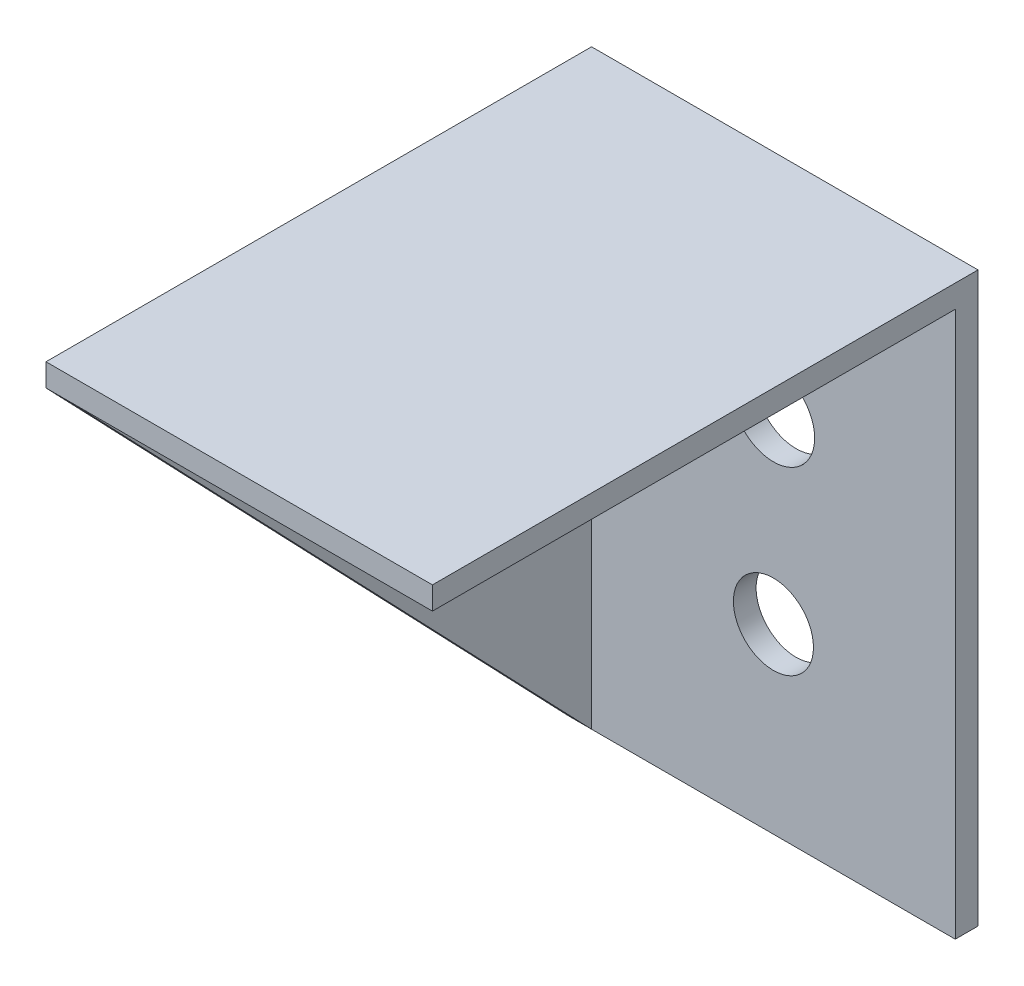
SolidWorks part; units mm, degrees
ref_plane "前视基准面" through (0, 0, 0) normal (0, 0, 1) x (1, 0, 0)
ref_plane "上视基准面" through (0, 0, 0) normal (0, 1, 0) x (1, 0, 0)
ref_plane "右视基准面" through (0, 0, 0) normal (1, 0, 0) x (0, 0, -1)
sketch "草图1" plane through (0, 0, 0) normal (0, 0, 1) x (1, 0, 0)
  line L1 (-1.8531, 2.9266) -> (0.1469, 2.9266)
  line L2 (-1.8531, 2.9266) -> (-1.8531, -0.0734)
  line L3 (-1.8531, -0.0734) -> (0.1469, -0.0734)
  line L4 (0.1469, 2.9266) -> (0.1469, -0.0734)
  line L5 (-1.8531, 2.9266) -> (0.1469, -0.0734) construction
  line L6 (-1.8531, -0.0734) -> (0.1469, 2.9266) construction
  point P0 (-0.8531, 1.4266)
  dimension "D1" = 3
  dimension "D2" = 2
extrude "凸台-拉伸1" add sketch "草图1" along normal blind 0.125
sketch "草图2" plane through (0, 2.9266, 0) normal (0, 1, 0) x (1, 0, 0)
  line L1 (-1.8531, 0) -> (0.1469, 0)
  line L2 (-1.8531, 0) -> (-1.8531, -3)
  line L3 (-1.8531, -3) -> (0.1469, -3)
  line L4 (0.1469, 0) -> (0.1469, -3)
  dimension "D1" = 2
  dimension "D2" = 3
extrude "凸台-拉伸2" add sketch "草图2" along normal blind 0.125
sketch "草图3" plane through (-1.8531, 0, 0) normal (-1, 0, 0) x (0, 0, 1)
  line L0 (0, 3.0516) -> (0, -0.0734)
  line L1 (0, -0.0734) -> (0.125, -0.0734)
  line L2 (0.125, -0.0734) -> (3, 2.9266)
  line L3 (3, 2.9266) -> (3, 3.0516)
  line L4 (3, 3.0516) -> (0, 3.0516)
extrude "凸台-拉伸3" add sketch "草图3" along normal blind 0.125
sketch "草图4" plane through (0, 0, 0.125) normal (0, 0, 1) x (1, 0, 0)
  line L0 (-1.8531, 2.9266) -> (-1.8531, -0.0734) construction
  line L1 (-1.8531, -0.0734) -> (0.1469, -0.0734) construction
  circle A0 centre (-0.8531, 0.9266) radius 0.2201
  circle A1 centre (-0.8531, 1.9266) radius 0.2267
  point P8 (-1.581, 1.18)
  point P9 (0, 0)
  dimension "D1" = 1
  dimension "D2" = 1
  dimension "D3" = 1
extrude "切除-拉伸1" cut sketch "草图4" against normal through all
